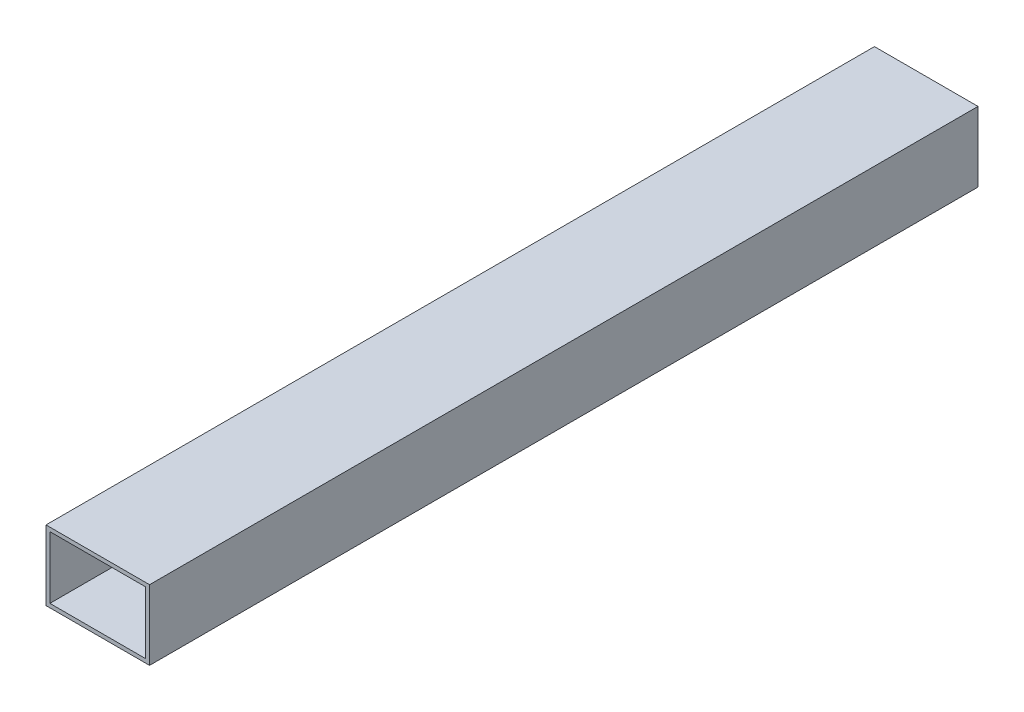
SolidWorks part; units mm, degrees
material "AISI 1020 Acier laminé à froid"
ref_plane "Plan de face" through (0, 0, 0) normal (0, 0, 1) x (1, 0, 0)
ref_plane "Plan de dessus" through (0, 0, 0) normal (0, 1, 0) x (1, 0, 0)
ref_plane "Plan de droite" through (0, 0, 0) normal (1, 0, 0) x (0, 0, -1)
sketch "Esquisse1" plane through (0, 0, 0) normal (0, 0, 1) x (1, 0, 0)
  line L1 (0, 0) -> (40, 0)
  line L2 (0, 0) -> (0, 27)
  line L3 (0, 27) -> (40, 27)
  line L4 (40, 0) -> (40, 27)
  line L5 (1.5, 25.5) -> (38.5, 25.5)
  line L6 (1.5, 25.5) -> (1.5, 1.5)
  line L7 (1.5, 1.5) -> (38.5, 1.5)
  line L8 (38.5, 25.5) -> (38.5, 1.5)
  dimension "D1" = 40
  dimension "D2" = 27
  dimension "D3" = 1.5
  dimension "D4" = 1.5
  dimension "D5" = 1.5
  dimension "D6" = 1.5
extrude "Boss.-Extru.1" add sketch "Esquisse1" along normal blind 320
